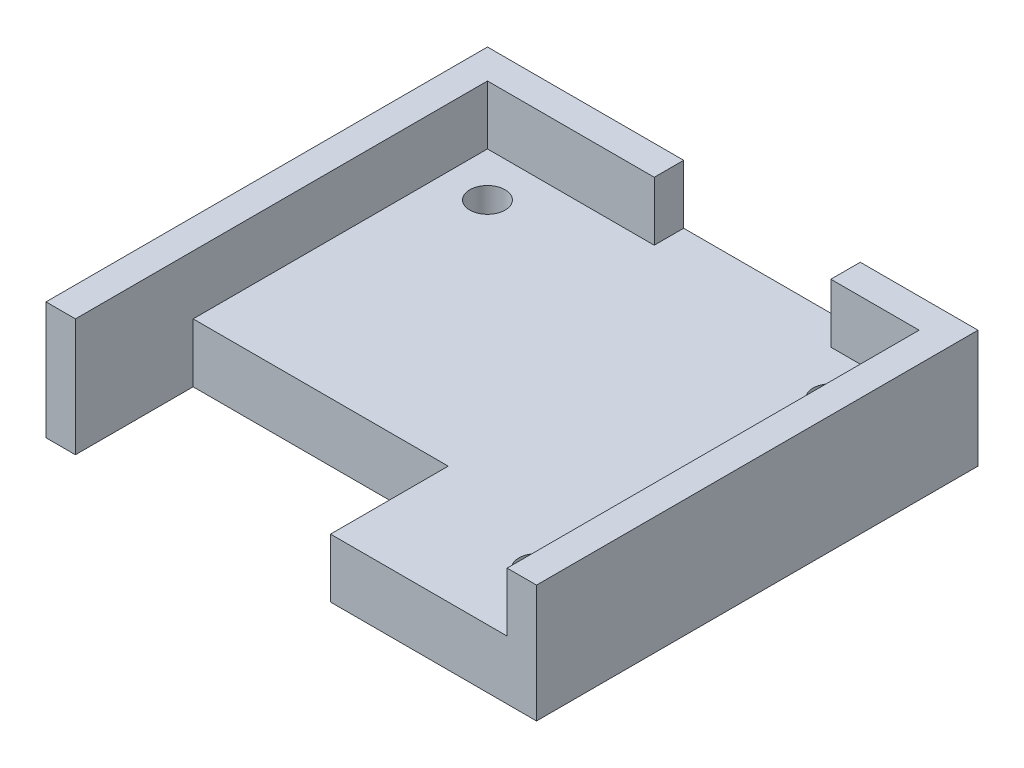
SolidWorks part; units mm, degrees
ref_plane "前视基准面" through (0, 0, 0) normal (0, 0, 1) x (1, 0, 0)
ref_plane "上视基准面" through (0, 0, 0) normal (0, 1, 0) x (1, 0, 0)
ref_plane "右视基准面" through (0, 0, 0) normal (1, 0, 0) x (0, 0, -1)
sketch "草图1" plane through (0, 0, 0) normal (0, 1, 0) x (1, 0, 0)
  line L1 (-25, 22.5) -> (25, 22.5)
  line L2 (-25, 22.5) -> (-25, -22.5)
  line L3 (-25, -22.5) -> (25, -22.5)
  line L4 (25, 22.5) -> (25, -22.5)
  line L5 (0, -22.5) -> (0, 22.5) construction
  line L6 (-25, 0) -> (25, 0) construction
  point P0 (0, 0)
  dimension "D1" = 45
  dimension "D2" = 50
extrude "凸台-拉伸1" add sketch "草图1" along normal blind 12
shell "抽壳1" thickness 3
hole_wizard "打孔尺寸(%根据)内六角圆柱头螺钉的类型1" positions "3D草图1" profile "草图3" counterbore size "M3" standard "GB" end condition through all
sketch3d "3D草图1"
  line L0 (17.5, 0, 15) -> (17.5, 0, -22.5) construction
  line L1 (25, 0, -22.5) -> (-25, 0, -22.5) construction
  line L3 (-17.5, 0, 15) -> (29.8897, 0, 15) construction
  line L4 (17.5, 0, -15) -> (-33.244, 0, -15) construction
  line L5 (-17.5, 0, 18.9882) -> (-17.5, 0, -26.1727) construction
  line L7 (0, 0, 0) -> (0, 0, 26.822) construction
  line L10 (0, 0, 0) -> (35.8238, 0, 0) construction
  point P0 (-17.5, 0, 15)
  point P2 (17.5, 0, 15)
  point P4 (17.5, 0, -15)
  point P6 (-17.5, 0, -15)
  dimension "D1" = 35
  dimension "D2" = 17.5
  dimension "D3" = 30
  dimension "D4" = 15
sketch "草图3" plane through (-17.5, 0, 15) normal (1, 0, 0) x (0, 0, -1)
  line L0 (0, 0) -> (0, 12)
  line L1 (0, 12) -> (1.8, 12)
  line L3 (1.8, 12) -> (1.8, 3.4)
  line L4 (3, 3.4) -> (1.8, 3.4)
  line L5 (3, 3.4) -> (3, 0.025)
  line L6 (3, 0.025) -> (3.025, 0)
  line L7 (3.025, 0) -> (0, 0)
  line L8 (-3, 0.025) -> (-3.025, 0) construction
  line L11 (0, -6.35) -> (0, 107.95) construction
  dimension "通孔孔直径" = 3.6
  dimension "通孔孔深度" = 12
  dimension "柱形沉头孔直径" = 6
  dimension "柱形沉头孔深度" = 3.4
  dimension "近端锥形沉头孔直径" = 6.05
  dimension "近端锥形沉头孔角度" = 90
sketch "草图4" plane through (0, 0, 22.5) normal (0, 0, 1) x (1, 0, 0)
  line L0 (-25, 12) -> (25, 12) construction
  line L1 (13, 12) -> (-5, 12)
  line L2 (13, 12) -> (13, 6)
  line L3 (13, 6) -> (-5, 6)
  line L4 (-5, 12) -> (-5, 6)
  line L5 (25, 12) -> (25, 0) construction
  dimension "D1" = 6
  dimension "D2" = 18
  dimension "D3" = 12
extrude "切除-拉伸1" cut sketch "草图4" against normal blind 12 from offset 40 offset against normal yes
sketch "草图5" plane through (0, 0, 22.5) normal (0, 0, 1) x (1, 0, 0)
  line L0 (-25, 12) -> (25, 12) construction
  line L1 (-22, 12) -> (22, 12)
  line L2 (-22, 12) -> (-22, 6)
  line L3 (-22, 6) -> (22, 6)
  line L4 (22, 12) -> (22, 6)
  line L5 (-25, 12) -> (-25, 0) construction
  dimension "D1" = 6
  dimension "D2" = 44
  dimension "D3" = 3
extrude "切除-拉伸2" cut sketch "草图5" against normal blind 12
sketch "草图6" plane through (0, 6, 0) normal (0, 1, 0) x (1, 0, 0)
  line L1 (-22, -22.5) -> (4, -22.5)
  line L2 (-22, -22.5) -> (-22, -10.5)
  line L3 (-22, -10.5) -> (4, -10.5)
  line L4 (4, -22.5) -> (4, -10.5)
  dimension "D1" = 12
  dimension "D2" = 26
extrude "切除-拉伸3" cut sketch "草图6" against normal blind 12
